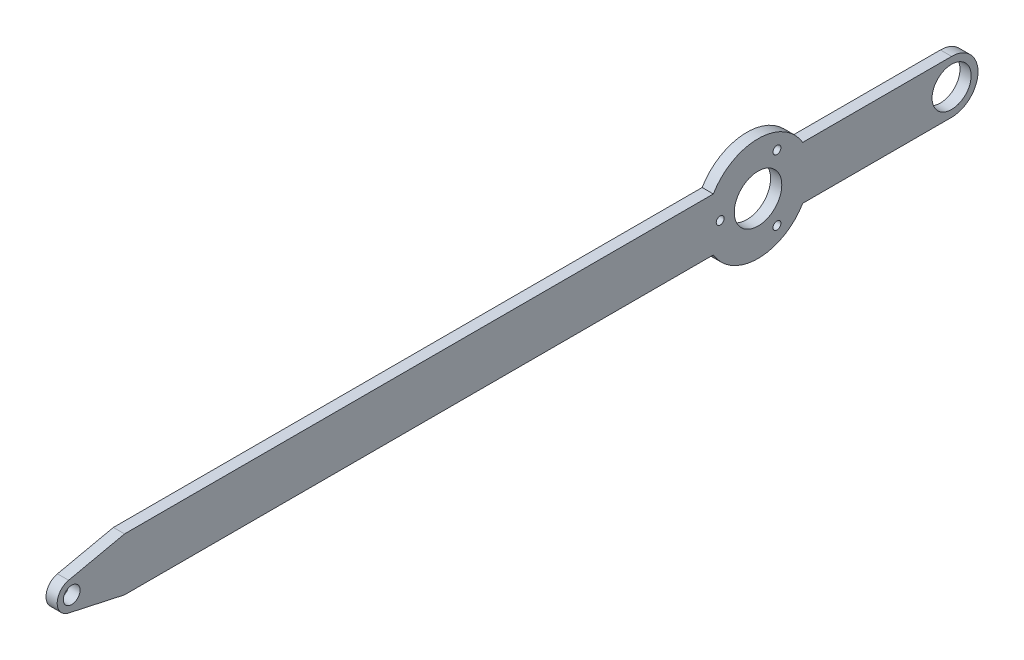
SolidWorks part; units mm, degrees
ref_plane "Front Plane" through (0, 0, 0) normal (0, 0, 1) x (1, 0, 0)
ref_plane "Top Plane" through (0, 0, 0) normal (0, 1, 0) x (1, 0, 0)
ref_plane "Right Plane" through (0, 0, 0) normal (1, 0, 0) x (0, 0, -1)
sketch "Sketch1" plane through (0, 0, 0) normal (1, 0, 0) x (0, 0, -1)
  line L0 (-470, 15) -> (-501.7607, 8.0727)
  line L1 (-470, 15) -> (0, 15)
  line L2 (-470, 15) -> (-470, -15) construction
  line L3 (-470, -15) -> (0, -15)
  line L4 (0, 15) -> (0, 11.1125) construction
  line L5 (-470, -15) -> (-501.7607, -8.0727)
  line L6 (0, 11.1125) -> (0, -11.1125) construction
  line L7 (0, -11.1125) -> (0, -15) construction
  circle A0 centre (-110, 0) radius 13.5
  circle A1 centre (0, 0) radius 11.1125
  circle A2 centre (-500, 0) radius 4.7625
  circle A3 centre (-110, 0) radius 29.5
  arc A4 (-501.7607, 8.0727) -> (-501.7607, -8.0727) centre (-500, 0) ccw
  arc A5 (-501.7607, -8.0727) -> (-501.7607, 8.0727) centre (-500, 0) ccw construction
  arc A7 (0, 15) -> (0, -15) centre (0, 0) cw
  point P10 (-97.4396, -27.1195)
  point P13 (-470, 0)
  dimension "D3" = 22.225
  dimension "D4" = 9.525
  dimension "D5" = 27
  dimension "D6" = 59
  dimension "D7" = 3.5
  dimension "D1" = 500
  dimension "D2" = 110
  dimension "D8" = 30
  dimension "D9" = 30
extrude "Boss-Extrude1" add sketch "Sketch1" along normal mid plane 6.35 contours L0 A4 L5 L3 A3 L1 A2 | L3 A3 | L1 A3 L3 A0 | L1 A3 | A7 L1 A3 L3 A1
hole_wizard "M4 Clearance Hole1" positions "Sketch2" profile "Sketch3" hole size "M4" standard "ANSI Metric" end condition through all
sketch "Sketch2" plane through (3.175, 0, 0) normal (1, 0, 0) x (0, 0, -1)
  line L0 (-110, 0) -> (-131.5, 0) construction
  line L1 (-110, 0) -> (-99.25, 18.6195) construction
  line L2 (-110, 0) -> (-99.25, -18.6195) construction
  point P2 (-131.5, 0)
  point P12 (-99.25, 18.6195)
  point P13 (-99.25, -18.6195)
  point P14 (-110, 0)
  dimension "D1" = 21.5
  dimension "D3" = 110
  dimension "D2" = 3
sketch "Sketch3" plane through (3.175, 0, 110) normal (0, 1, 0) x (0, 0, -1)
  line L0 (0, 0) -> (0, 6.35)
  line L1 (0, 6.35) -> (2.25, 6.35)
  line L2 (2.25, 6.35) -> (2.25, 0)
  line L5 (2.25, 0) -> (0, 0)
  line L11 (0, -6.35) -> (0, 107.95) construction
  dimension "Thru Hole Dia." = 4.5
  dimension "Thru Hole Depth" = 6.35
